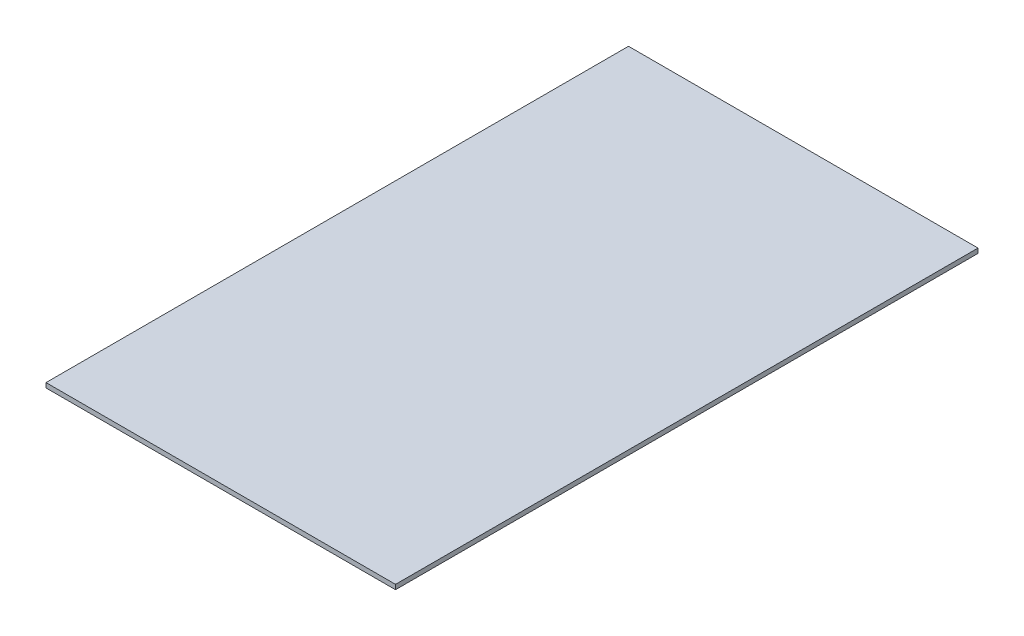
SolidWorks part; units mm, degrees
ref_plane "Front Plane" through (0, 0, 0) normal (0, 0, 1) x (1, 0, 0)
ref_plane "Top Plane" through (0, 0, 0) normal (0, 1, 0) x (1, 0, 0)
ref_plane "Right Plane" through (0, 0, 0) normal (1, 0, 0) x (0, 0, -1)
sketch "Sketch1" plane through (0, 0, 0) normal (0, 1, 0) x (1, 0, 0)
  line L1 (-225, -375) -> (225, -375)
  line L2 (-225, -375) -> (-225, 375)
  line L3 (-225, 375) -> (225, 375)
  line L4 (225, -375) -> (225, 375)
  line L5 (-225, -375) -> (225, 375) construction
  line L6 (-225, 375) -> (225, -375) construction
  point P0 (0, 0)
  dimension "D1" = 450
  dimension "D2" = 750
extrude "Boss-Extrude1" add sketch "Sketch1" along normal blind 6
